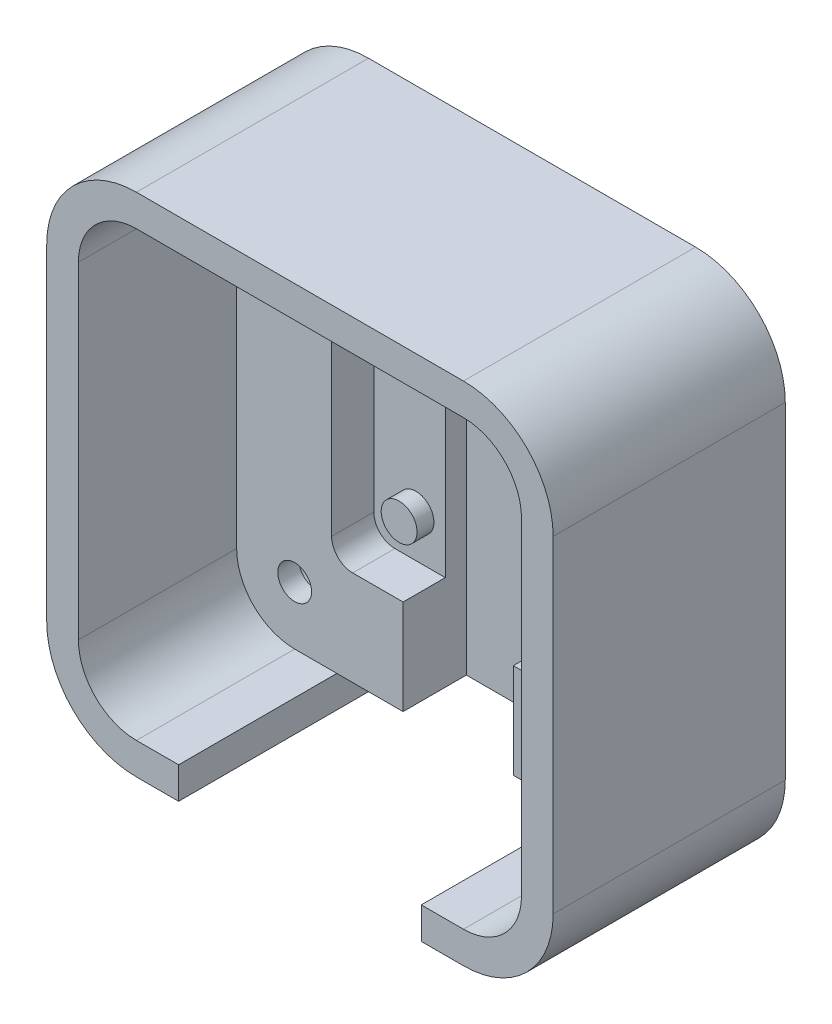
SolidWorks part; units mm, degrees
ref_plane "Plano frontal" through (0, 0, 0) normal (0, 0, 1) x (1, 0, 0)
ref_plane "Plano superior" through (0, 0, 0) normal (0, 1, 0) x (1, 0, 0)
ref_plane "Plano direito" through (0, 0, 0) normal (1, 0, 0) x (0, 0, -1)
sketch "Esboço1" plane through (0, 0, 0) normal (0, 0, 1) x (1, 0, 0)
  line L1 (15.5, -21) -> (-15.5, -21)
  line L2 (21, -15.5) -> (21, 15.5)
  line L3 (15.5, 21) -> (-15.5, 21)
  line L4 (-21, -15.5) -> (-21, 15.5)
  line L5 (21, -21) -> (-21, 21) construction
  line L6 (21, 21) -> (-21, -21) construction
  arc A0 (-15.5, -21) -> (-21, -15.5) centre (-15.5, -15.5) cw
  arc A1 (15.5, -21) -> (21, -15.5) centre (15.5, -15.5) ccw
  arc A2 (21, 15.5) -> (15.5, 21) centre (15.5, 15.5) ccw
  arc A3 (-15.5, 21) -> (-21, 15.5) centre (-15.5, 15.5) ccw
  point P0 (0, 0)
  dimension "D2" = 5.5
  dimension "D1" = 42
extrude "Ressalto-extrusão1" add sketch "Esboço1" along normal blind 7
sketch "Esboço2" plane through (0, 0, 0) normal (0, 0, -1) x (-1, 0, 0)
  line L1 (10, -12) -> (-10, -12)
  line L2 (12, -10) -> (12, 10)
  line L3 (10, 12) -> (-10, 12)
  line L4 (-12, -10) -> (-12, 10)
  line L5 (12, -12) -> (-12, 12) construction
  line L6 (12, 12) -> (-12, -12) construction
  arc A0 (-10, -12) -> (-12, -10) centre (-10, -10) cw
  arc A1 (10, -12) -> (12, -10) centre (10, -10) ccw
  arc A2 (12, 10) -> (10, 12) centre (10, 10) ccw
  arc A3 (-10, 12) -> (-12, 10) centre (-10, 10) ccw
  point P0 (0, 0)
  dimension "D2" = 2
  dimension "D1" = 24
extrude "Corte-extrusão1" cut sketch "Esboço2" against normal through all
sketch "Esboço3" plane through (0, 0, 0) normal (0, 0, -1) x (-1, 0, 0)
  line L0 (-5.225, 12) -> (-5.225, -12)
  line L1 (10, 12) -> (-10, 12) construction
  line L2 (-10, -12) -> (10, -12) construction
  line L16 (0, 3.85) -> (0, -3.85) construction
  line L17 (5.225, 12) -> (10, 12)
  line L18 (12, 10) -> (12, -10)
  line L19 (-10, -12) -> (10, -12)
  line L20 (-12, 10) -> (-12, -10)
  line L21 (10, 12) -> (-10, 12)
  line L22 (-10, -12) -> (-5.225, -12)
  line L23 (-12, 10) -> (-12, -10)
  line L24 (-5.225, 12) -> (-10, 12)
  line L25 (10, -12) -> (5.225, -12)
  line L26 (5.225, 12) -> (5.225, -12)
  circle A10 centre (-8, 8) radius 1.775 construction
  arc A11 (10, 12) -> (12, 10) centre (10, 10) cw
  arc A12 (-12, -10) -> (-10, -12) centre (-10, -10) ccw
  arc A13 (-10, 12) -> (-12, 10) centre (-10, 10) ccw
  arc A14 (-12, -10) -> (-10, -12) centre (-10, -10) ccw
  arc A15 (-10, 12) -> (-12, 10) centre (-10, 10) ccw
  arc A16 (12, -10) -> (10, -12) centre (10, -10) cw
  dimension "D2" = 1
  dimension "D1" = 0
extrude "Ressalto-extrusão2" add sketch "Esboço3" against normal blind 3
sketch "Esboço4" plane through (0, 0, 3) normal (0, 0, 1) x (1, 0, 0)
  circle A0 centre (-8, 8) radius 1.7
  circle A1 centre (8, 8) radius 1.7
  circle A2 centre (8, -8) radius 1.7
  circle A3 centre (-8, -8) radius 1.7
  dimension "D1" = 3.4
extrude "Ressalto-extrusão3" add sketch "Esboço4" along normal blind 1.6
sketch "Esboço5" plane through (0, -21, 0) normal (0, -1, 0) x (1, 0, 0)
  line L0 (-15.5, 0) -> (15.5, 0) construction
  line L5 (-15.5, 7) -> (15.5, 7) construction
  line L6 (-5.225, 1) -> (5.225, 1)
  line L7 (-5.225, 1) -> (-5.225, 7)
  line L8 (-5.225, 7) -> (5.225, 7)
  line L9 (5.225, 1) -> (5.225, 7)
  point P6 (0, 1)
  dimension "D1" = 1
  dimension "D2" = 10.45
extrude "Corte-extrusão2" cut sketch "Esboço5" against normal up to next
sketch "Esboço6" plane through (0, 0, 0) normal (0, 0, -1) x (-1, 0, 0)
  line L1 (-5.225, 12) -> (5.225, 12)
  line L2 (-5.225, 12) -> (-5.225, -12)
  line L3 (-5.225, -12) -> (5.225, -12)
  line L4 (5.225, 12) -> (5.225, -12)
extrude "Ressalto-extrusão4" add sketch "Esboço6" against normal blind 1
sketch "Esboço8" plane through (0, 0, 7) normal (0, 0, 1) x (1, 0, 0)
  line L0 (0, -3.85) -> (0, 3.85) construction
  line L1 (3.85, 0) -> (-3.85, 0) construction
  circle A0 centre (-15.5, 15.5) radius 1.6
  circle A1 centre (15.5, 15.5) radius 1.6
  circle A2 centre (15.5, -15.5) radius 1.6
  circle A3 centre (-15.5, -15.5) radius 1.6
  dimension "D1" = 3.2
extrude "Corte-extrusão3" cut sketch "Esboço8" against normal up to next
sketch "Esboço11" plane through (0, 0, 0) normal (0, 0, -1) x (-1, 0, 0)
  line L0 (0, 3.85) -> (0, -3.85) construction
  line L1 (3.85, 0) -> (-3.85, 0) construction
  circle A0 centre (-15.5, 15.5) radius 2.9
  circle A1 centre (15.5, 15.5) radius 2.9
  circle A2 centre (15.5, -15.5) radius 2.9
  circle A3 centre (-15.5, -15.5) radius 2.9
  dimension "D1" = 5.8
extrude "Corte-extrusão4" cut sketch "Esboço11" against normal blind 5
ref_plane "Plano1" through (-11.325, -9.6, 3.014) normal (0, 1, 0) x (1, 0, 0)
sketch "Esboço13" plane through (0, 0, 0) normal (0, 0, -1) x (-1, 0, 0)
  line L30 (24, -15.5) -> (24, 15.5)
  line L31 (15.5, 24) -> (-15.5, 24)
  line L32 (-24, 15.5) -> (-24, -15.5)
  line L33 (-15.5, -24) -> (-11.5, -24)
  line L34 (21, -15.5) -> (21, 15.5)
  line L35 (-15.5, -21) -> (15.5, -21)
  line L36 (-21, 15.5) -> (-21, -15.5)
  line L37 (15.5, 21) -> (-15.5, 21)
  line L38 (21, -15.5) -> (21, 15.5)
  line L39 (-15.5, -21) -> (-11.5, -21)
  line L40 (-21, 15.5) -> (-21, -15.5)
  line L41 (15.5, 21) -> (-15.5, 21)
  line L42 (-11.5, -21) -> (-11.5, -24)
  line L43 (11.5, -21) -> (11.5, -24)
  line L44 (11.5, -24) -> (15.5, -24)
  line L45 (11.5, -21) -> (15.5, -21)
  line L46 (-15.5, -24) -> (15.5, -24) construction
  line L48 (-15.5, -21) -> (15.5, -21) construction
  arc A10 (24, 15.5) -> (15.5, 24) centre (15.5, 15.5) ccw
  arc A11 (-15.5, 24) -> (-24, 15.5) centre (-15.5, 15.5) ccw
  arc A12 (-24, -15.5) -> (-15.5, -24) centre (-15.5, -15.5) ccw
  arc A13 (15.5, -24) -> (24, -15.5) centre (15.5, -15.5) ccw
  arc A14 (-15.5, 21) -> (-21, 15.5) centre (-15.5, 15.5) ccw
  arc A15 (21, 15.5) -> (15.5, 21) centre (15.5, 15.5) ccw
  arc A16 (15.5, -21) -> (21, -15.5) centre (15.5, -15.5) ccw
  arc A17 (-21, -15.5) -> (-15.5, -21) centre (-15.5, -15.5) ccw
  arc A18 (-15.5, 21) -> (-21, 15.5) centre (-15.5, 15.5) ccw
  arc A19 (21, 15.5) -> (15.5, 21) centre (15.5, 15.5) ccw
  arc A20 (15.5, -21) -> (21, -15.5) centre (15.5, -15.5) ccw
  arc A21 (-21, -15.5) -> (-15.5, -21) centre (-15.5, -15.5) ccw
  dimension "D3" = 4
  dimension "D4" = 4
  dimension "D1" = 0
  dimension "D2" = 3
extrude "Ressalto-extrusão5" add sketch "Esboço13" against normal blind 22
